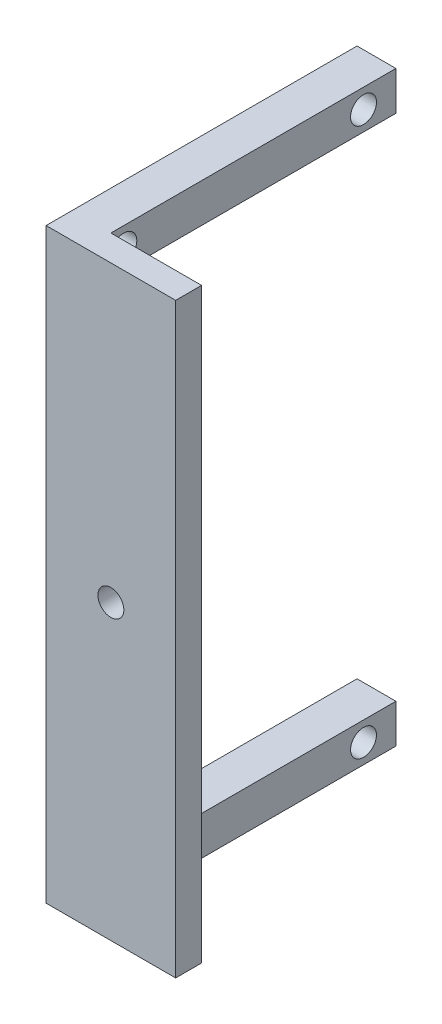
SolidWorks part; units mm, degrees
ref_plane "Front Plane" through (0, 0, 0) normal (0, 0, 1) x (1, 0, 0)
ref_plane "Top Plane" through (0, 0, 0) normal (0, 1, 0) x (1, 0, 0)
ref_plane "Right Plane" through (0, 0, 0) normal (1, 0, 0) x (0, 0, -1)
sketch "Sketch1" plane through (0, 0, 0) normal (0, 0, 1) x (1, 0, 0)
  line L1 (7.5935, -16.527) -> (-2.4065, -16.527)
  line L2 (7.5935, -16.527) -> (7.5935, 28.773)
  line L3 (7.5935, 28.773) -> (-2.4065, 28.773)
  line L4 (-2.4065, -16.527) -> (-2.4065, 28.773)
  line L5 (7.5935, -16.527) -> (-2.4065, 28.773) construction
  line L6 (7.5935, 28.773) -> (-2.4065, -16.527) construction
  point P0 (2.5935, 6.123)
extrude "Boss-Extrude2" add sketch "Sketch1" along normal blind 2
sketch "Sketch2" plane through (0, 0, 0) normal (0, 0, -1) x (-1, 0, 0)
  line L0 (2.4065, -16.527) -> (-7.5935, -16.527) construction
  line L1 (-0.5935, 28.773) -> (2.4065, 28.773)
  line L2 (-0.5935, 28.773) -> (-0.5935, 25.773)
  line L3 (-0.5935, 25.773) -> (2.4065, 25.773)
  line L4 (2.4065, 28.773) -> (2.4065, 25.773)
  line L5 (-0.5935, 28.773) -> (2.4065, 25.773) construction
  line L6 (-0.5935, 25.773) -> (2.4065, 28.773) construction
  line L7 (-0.5935, -13.527) -> (2.4065, -13.527)
  line L8 (-0.5935, -13.527) -> (-0.5935, -16.527)
  line L9 (-0.5935, -16.527) -> (2.4065, -16.527)
  line L10 (2.4065, -13.527) -> (2.4065, -16.527)
  line L11 (-0.5935, -13.527) -> (2.4065, -16.527) construction
  line L12 (-0.5935, -16.527) -> (2.4065, -13.527) construction
  line L13 (2.4065, 28.773) -> (2.4065, -16.527) construction
  line L14 (-7.5935, 28.773) -> (2.4065, 28.773) construction
  point P0 (0.9065, 27.273)
  point P5 (0.9065, -15.027)
  dimension "D1" = 0
  dimension "D2" = 0
  dimension "D3" = 0
  dimension "D4" = 0
extrude "Boss-Extrude3" add sketch "Sketch2" along normal blind 22
sketch "Sketch3" plane through (-2.4065, 0, 0) normal (-1, 0, 0) x (0, 0, 1)
  line L0 (0, 25.773) -> (0, -13.527) construction
  line L1 (2, -16.527) -> (-22, -16.527) construction
  line L2 (2, 28.773) -> (-22, 28.773) construction
  circle A0 centre (-19.5, 27.273) radius 1
  circle A1 centre (-1, 27.273) radius 1
  circle A2 centre (-1, -15.027) radius 1
  circle A3 centre (-19.5, -15.027) radius 1
  dimension "D1" = 1
  dimension "D2" = 1
  dimension "D3" = 18.5
  dimension "D5" = 1.5
  dimension "D4" = 18.5
  dimension "D6" = 1.5
  dimension "D7" = 1.5
  dimension "D8" = 1.5
extrude "Cut-Extrude1" cut sketch "Sketch3" against normal blind 22
sketch "Sketch4" plane through (0, 0, 0) normal (0, 0, -1) x (-1, 0, 0)
  line L1 (2.4065, 25.773) -> (2.4065, -13.527) construction
  line L2 (-0.5935, -16.527) -> (-7.5935, -16.527) construction
  circle A0 centre (-2.5935, 6.073) radius 1
  point P6 (-6.028, -12.4444)
  dimension "D1" = 5
  dimension "D2" = 22.6
extrude "Cut-Extrude2" cut sketch "Sketch4" against normal blind 22 contours A0
